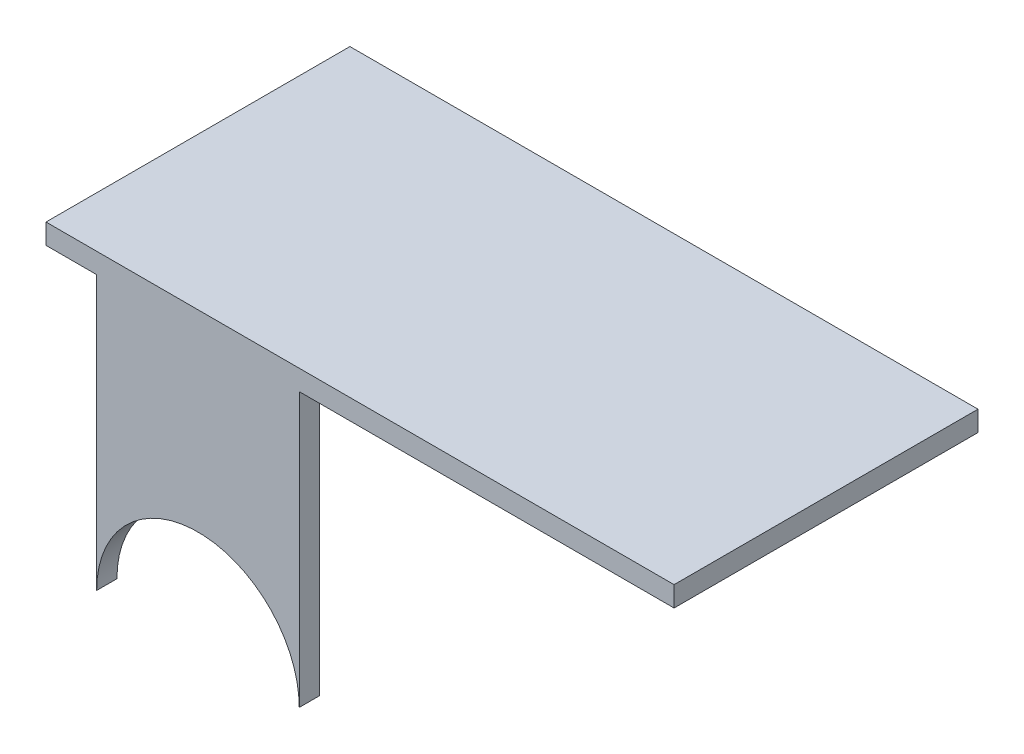
SolidWorks part; units mm, degrees
ref_plane "Front Plane" through (0, 0, 0) normal (0, 0, 1) x (1, 0, 0)
ref_plane "Top Plane" through (0, 0, 0) normal (0, 1, 0) x (1, 0, 0)
ref_plane "Right Plane" through (0, 0, 0) normal (1, 0, 0) x (0, 0, -1)
sketch "Sketch2" plane through (0, 0, 0) normal (0, 0, 1) x (1, 0, 0)
  line L0 (-44.925, -5.1312) -> (-44.925, 21.8688)
  line L1 (-44.925, 21.8688) -> (-24.925, 21.8688)
  line L2 (-24.925, 21.8688) -> (-24.925, -5.1312)
  arc A1 (-44.925, -5.1312) -> (-24.925, -5.1312) centre (-34.925, -5.1312) cw
  dimension "D1" = 10
  dimension "D2" = 27
  dimension "D3" = 27
  dimension "D4" = 20
extrude "Boss-Extrude1" add sketch "Sketch2" along normal blind 2
sketch "Sketch3" plane through (0, 21.8688, 0) normal (0, 1, 0) x (1, 0, 0)
  line L0 (-44.925, -2) -> (-49.925, -2)
  line L1 (-44.925, -2) -> (12.075, -2)
  line L3 (-49.925, 28) -> (12.075, 28)
  line L4 (12.075, -2) -> (12.075, 28)
  line L5 (-49.925, -2) -> (-49.925, 28)
  dimension "D1" = 5
  dimension "D2" = 30
  dimension "D3" = 62
extrude "Boss-Extrude2" add sketch "Sketch3" along normal blind 2
